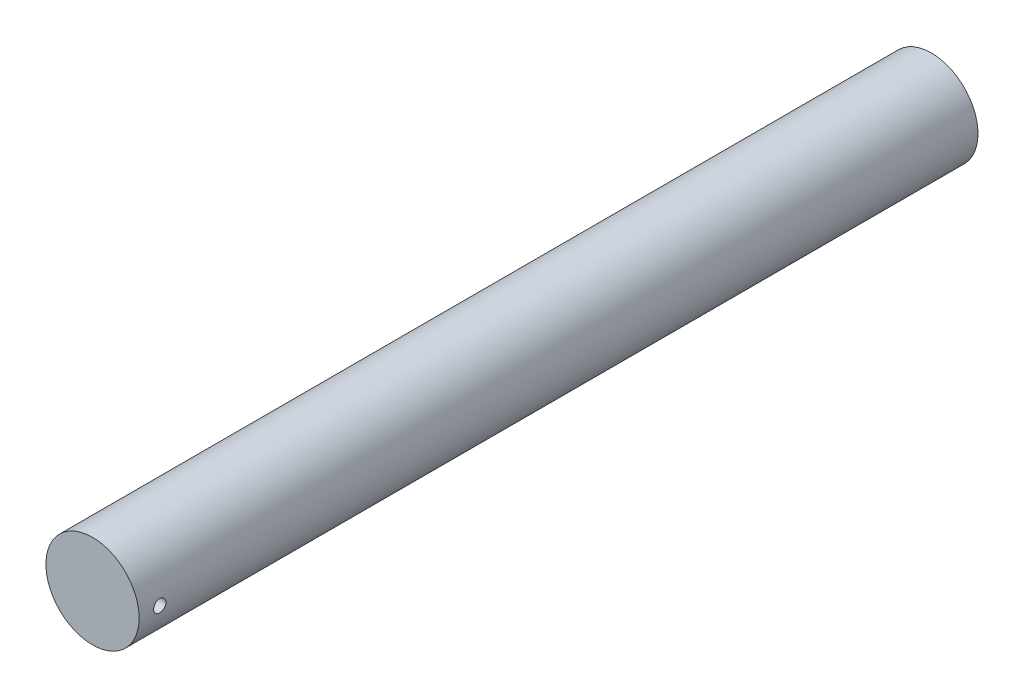
SolidWorks part; units mm, degrees
material "AISI 1020"
ref_plane "Front Plane" through (0, 0, 0) normal (0, 0, 1) x (1, 0, 0)
ref_plane "Top Plane" through (0, 0, 0) normal (0, 1, 0) x (1, 0, 0)
ref_plane "Right Plane" through (0, 0, 0) normal (1, 0, 0) x (0, 0, -1)
other "Configuration Table"
sketch "Sketch1" plane through (0, 0, 0) normal (0, 0, 1) x (1, 0, 0)
  circle A0 centre (0, 0) radius 3.81
  dimension "D1" = 7.62
extrude "Boss-Extrude1" add sketch "Sketch1" along normal mid plane 68.58
scale "Scale1" scale about centroid uniform scaling yes scale factor 1.5
sketch "Sketch2" plane through (0, 0, 0) normal (1, 0, 0) x (0, 0, -1)
  line L0 (-51.435, 5.715) -> (-51.435, -5.715) construction
  circle A0 centre (-48.895, 0) radius 0.762
  dimension "D2" = 1.524
  dimension "D1" = 2.54
extrude "Cut-Extrude1" cut sketch "Sketch2" along normal through all
ref_plane "Plane1" through (0, 0, 0) normal (0.7071, 0.7071, 0) x (-0.7071, 0.7071, 0)
sketch "Sketch3" plane through (0, 0, 0) normal (0.7071, 0.7071, 0) x (-0.7071, 0.7071, 0)
  line L0 (-4.0411, 48.895) -> (0, 48.895) construction
  line L1 (0, 51.435) -> (0, -51.435) construction
  circle A0 centre (0, -5.715) radius 1.397
  dimension "D2" = 2.794
  dimension "D1" = 54.61
extrude "Cut-Extrude2" cut sketch "Sketch3" against normal through all
